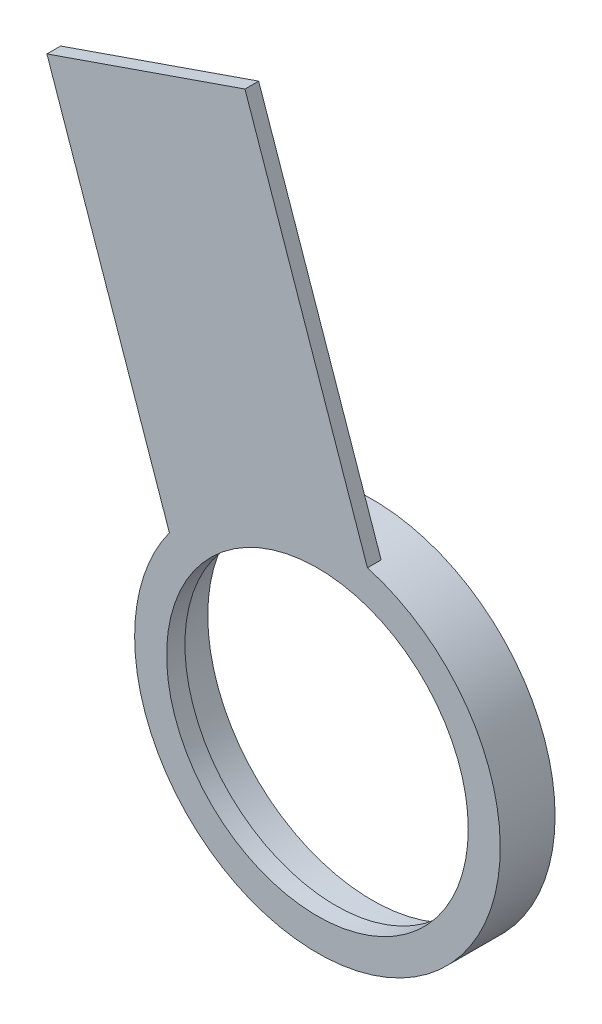
SolidWorks part; units mm, degrees
ref_plane "前视基准面" through (0, 0, 0) normal (0, 0, 1) x (1, 0, 0)
ref_plane "上视基准面" through (0, 0, 0) normal (0, 1, 0) x (1, 0, 0)
ref_plane "右视基准面" through (0, 0, 0) normal (1, 0, 0) x (0, 0, -1)
other "Configuration Table"
sketch "草图1" plane through (0, 0, 0) normal (0, 0, 1) x (1, 0, 0)
  circle A0 centre (-86.6066, -63.7835) radius 33
  circle A1 centre (-86.6066, -63.7835) radius 40
extrude "凸台-拉伸1" add sketch "草图1" along normal blind 4
sketch "草图2" plane through (0, 0, 0) normal (0, 0, -1) x (-1, 0, 0)
  circle A0 centre (86.6066, -63.7835) radius 40
  circle A1 centre (86.6066, -63.7835) radius 36
extrude "凸台-拉伸2" add sketch "草图2" along normal blind 8
sketch "草图4" plane through (0, 0, 4) normal (0, 0, 1) x (1, 0, 0)
  line L0 (-104.6153, -11.8154) -> (-86.6066, -63.7835) construction
  line L2 (-102.4707, 52.0258) -> (-145.8026, 37.0099)
  line L4 (-145.8026, 37.0099) -> (-118.2383, -42.5332)
  line L5 (-102.4707, 52.0258) -> (-74.9064, -27.5173)
  arc A8 (-118.2383, -42.5332) -> (-74.9064, -27.5173) centre (-86.6066, -63.7835) cw
  point P16 (-124.1366, 44.5179)
extrude "凸台-拉伸3" add sketch "草图4" against normal blind 3
